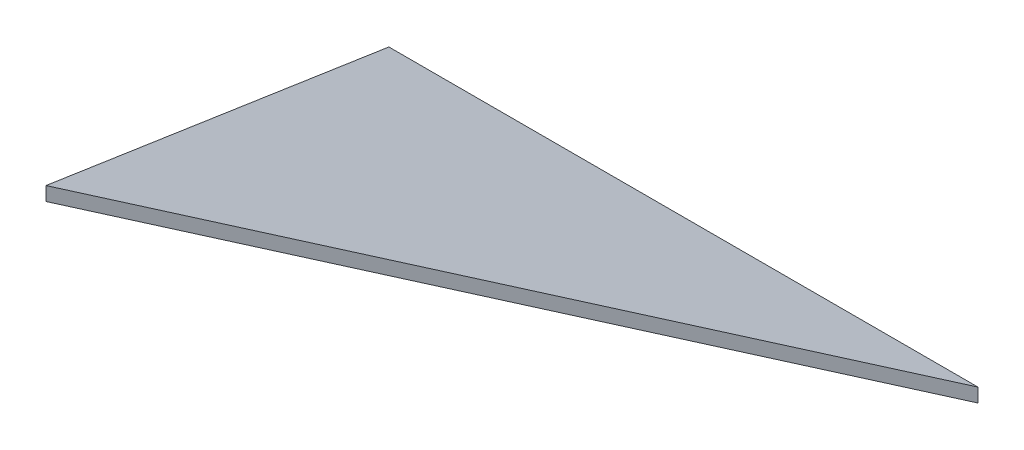
SolidWorks part; units mm, degrees
ref_plane "Front Plane" through (0, 0, 0) normal (0, 0, 1) x (1, 0, 0)
ref_plane "Top Plane" through (0, 0, 0) normal (0, 1, 0) x (1, 0, 0)
ref_plane "Right Plane" through (0, 0, 0) normal (1, 0, 0) x (0, 0, -1)
sketch "Sketch2" plane through (0, 0, 0) normal (0, 1, 0) x (1, 0, 0)
  line L0 (-57.15, 0) -> (224.536, 0)
  line L1 (224.536, 0) -> (-24.3577, -196.7539)
  line L2 (-24.3577, -196.7539) -> (-57.15, 0)
  line L3 (0, 0) -> (0, -152.4) construction
  line L4 (-31.75, -152.4) -> (31.75, -152.4) construction
  point P2 (0, 0)
  dimension "D1" = 281.686
  dimension "D2" = 57.15
  dimension "D3" = 63.5
  dimension "D4" = 152.4
extrude "Boss-Extrude1" add sketch "Sketch2" along normal blind 152.4
ref_plane "Plane1" through (-63.5, 0, 0) normal (1, 0, 0) x (0, 0, -1)
sketch "Sketch3" plane through (-63.5, 0, 0) normal (1, 0, 0) x (0, 0, -1)
  line L0 (0, 76.2) -> (-152.4, 76.2) construction
  line L1 (0, 152.4) -> (0, 0) construction
  line L2 (-152.4, 44.45) -> (-152.4, 107.95) construction
  line L3 (0, 152.4) -> (-152.4, 107.95)
  line L4 (0, 0) -> (-152.4, 44.45)
  line L5 (-152.4, 107.95) -> (-261.2571, 76.2)
  line L6 (-152.4, 44.45) -> (-261.2571, 76.2)
  line L7 (0, 152.4) -> (0, 0)
  point P7 (-152.4, 76.2)
  dimension "D1" = 152.4
  dimension "D2" = 63.5
extrude "Cut-Extrude2" cut sketch "Sketch3" along normal through all flip side to cut
shell "Shell1" thickness 6.35
ref_plane "Plane2" through (0, -12.7, 0) normal (0, 1, 0) x (1, 0, 0)
sketch "Sketch4" plane through (-63.5, 0, 0) normal (1, 0, 0) x (0, 0, -1)
  line L1 (0, 274.6116) -> (-196.7539, 217.2251)
  line L2 (-196.7539, 95.0134) -> (-196.7539, 57.3866) construction
  line L3 (-196.7539, 217.2251) -> (-196.7539, 95.0134) construction
  line L4 (-196.7539, 95.0134) -> (0, 152.4) construction
  line L5 (-196.7539, 57.3866) -> (0, 0) construction
  line L6 (0, 0) -> (0, 6.6146) construction
  line L7 (0, 6.6146) -> (-196.7539, 64.0011)
  line L8 (-196.7539, 64.0011) -> (-196.7539, 57.3866) construction
  line L9 (0, 274.6116) -> (0, 6.6146)
  line L10 (-196.7539, 64.0011) -> (-196.7539, 217.2251)
  dimension "D1" = 6.6146
extrude "Cut-Extrude3" cut sketch "Sketch4" along normal through all
